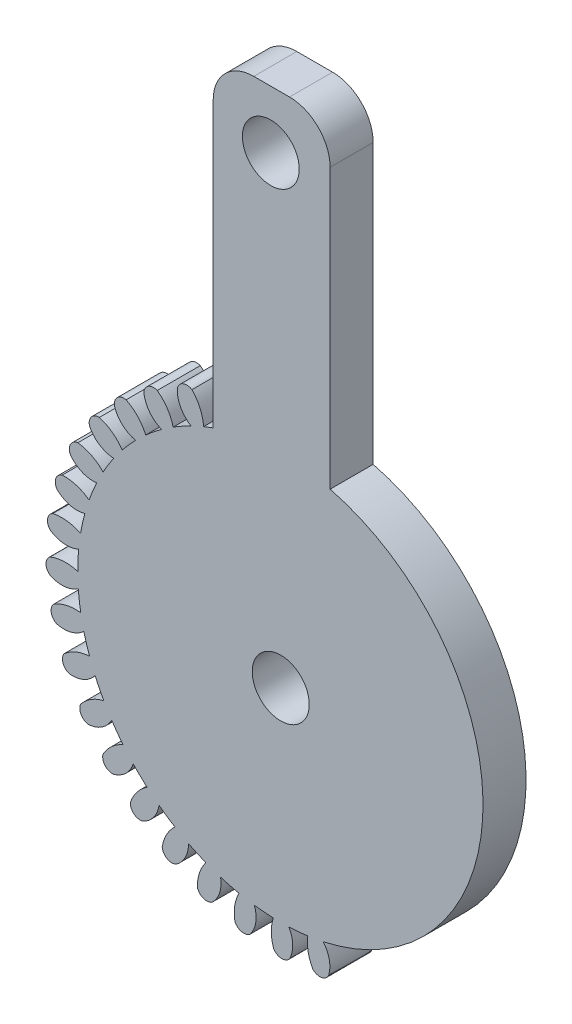
SolidWorks part; units mm, degrees
ref_plane "Front Plane" through (0, 0, 0) normal (0, 0, 1) x (1, 0, 0)
ref_plane "Top Plane" through (0, 0, 0) normal (0, 1, 0) x (1, 0, 0)
ref_plane "Right Plane" through (0, 0, 0) normal (1, 0, 0) x (0, 0, -1)
sketch "Sketch1" plane through (0, 0, 0) normal (0, 0, 1) x (1, 0, 0)
  circle A0 centre (0, 0) radius 12.5
  dimension "D1" = 25
extrude "Boss-Extrude1" add sketch "Sketch1" along normal blind 2.65
sketch "Sketch2" plane through (0, 0, 2.65) normal (0, 0, 1) x (1, 0, 0)
  line L0 (-1.49, 12.4109) -> (-0.6475, 12.4832)
  arc A0 (-0.6475, 12.4832) -> (-0.7866, 14.246) centre (-3.1184, 13.1752) ccw
  circle A1 centre (0, 0) radius 12.5 construction
  arc A2 (-0.7866, 14.246) -> (-1.7683, 14.1797) centre (-1.2544, 13.8712) ccw
  arc A3 (-1.7683, 14.1797) -> (-1.49, 12.4109) centre (-0.1418, 13.5293) ccw
extrude "Boss-Extrude2" add sketch "Sketch2" against normal blind 2.65
pattern_circular "CirPattern1" count 37 over 360 about axis through (-0.0056, 0.0621, 0) along (0, 0, 1) of "Boss-Extrude2"
sketch "Sketch3" plane through (0, 0, 2.65) normal (0, 0, 1) x (1, 0, 0)
  arc A0 (2.6173, -12.2229) -> (2.7074, 12.2033) centre (-0.0567, 0.0002) ccw
  arc A1 (3.1516, -14.6652) -> (3.2597, 14.6415) centre (-0.0567, 0.0002) ccw
  arc A2 (2.6173, -12.2229) -> (3.1516, -14.6652) centre (1.6634, -13.7112) cw
  arc A3 (3.2597, 14.6415) -> (2.7074, 12.2033) centre (4.2027, 13.1462) ccw
  dimension "D1" = 2.5
extrude "Cut-Extrude1" cut sketch "Sketch3" against normal blind 6
sketch "Sketch5" plane through (0, 0, 2.65) normal (0, 0, 1) x (1, 0, 0)
  line L1 (-4.1582, 11.7881) -> (3.0418, 11.7881)
  line L2 (-4.1582, 11.7881) -> (-4.1582, 31.7881)
  line L3 (-4.1582, 31.7881) -> (3.0418, 31.7881)
  line L4 (3.0418, 11.7881) -> (3.0418, 31.7881)
  arc A0 (-3.5567, 11.9833) -> (-4.749, 11.5627) centre (0, 0) ccw construction
  dimension "D1" = 20
  dimension "D2" = 7.2
extrude "Boss-Extrude3" add sketch "Sketch5" against normal blind 2.65
fillet "Fillet1" radius 2.5 2 edges at (3.0418, 31.7881, 1.325) (-4.1582, 31.7881, 1.325)
sketch "Sketch6" plane through (0, 0, 2.65) normal (0, 0, 1) x (1, 0, 0)
  circle A0 centre (0, 0) radius 1.755
  dimension "D1" = 3.51
extrude "Cut-Extrude2" cut sketch "Sketch6" against normal through all
sketch "Sketch7" plane through (0, 0, 2.65) normal (0, 0, 1) x (1, 0, 0)
  line L0 (0.5418, 31.7881) -> (-1.6582, 31.7881) construction
  circle A0 centre (-0.6121, 28.2381) radius 1.75
  dimension "D1" = 3.5
  dimension "D2" = 3.55
extrude "Cut-Extrude3" cut sketch "Sketch7" against normal through all
